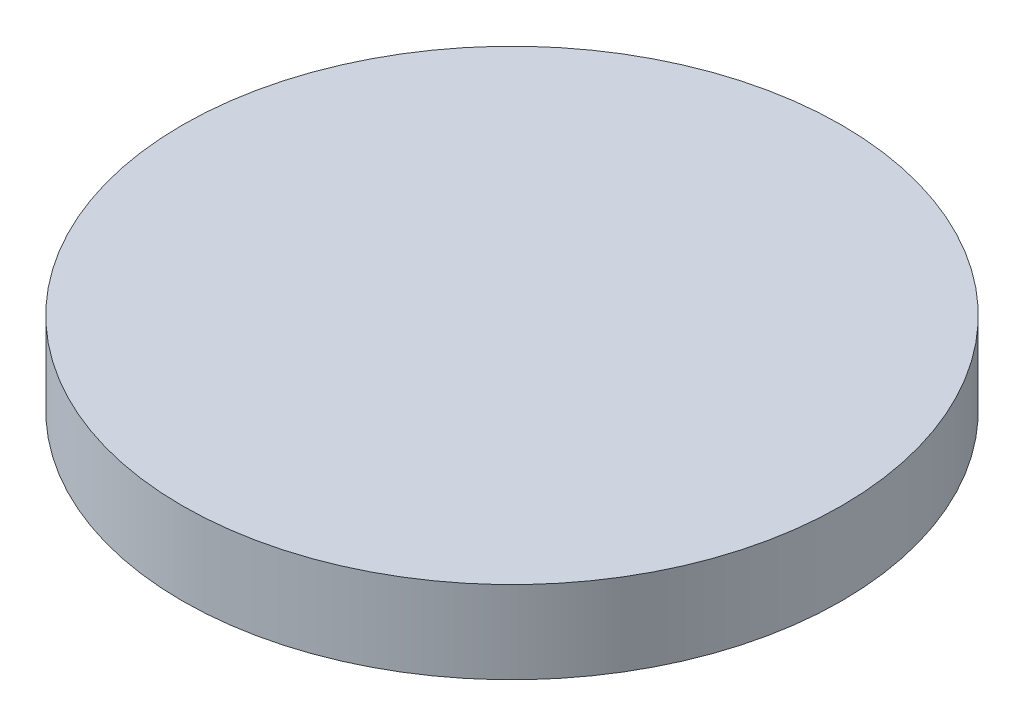
SolidWorks part; units mm, degrees
ref_plane "Front Plane" through (0, 0, 0) normal (0, 0, 1) x (1, 0, 0)
ref_plane "Top Plane" through (0, 0, 0) normal (0, 1, 0) x (1, 0, 0)
ref_plane "Right Plane" through (0, 0, 0) normal (1, 0, 0) x (0, 0, -1)
sketch "Sketch1" plane through (0, 0, 0) normal (0, 1, 0) x (1, 0, 0)
  circle A0 centre (0, 0) radius 101.6
  dimension "D1" = 203.2
extrude "Boss-Extrude1" add sketch "Sketch1" along normal blind 25.4
sketch "Sketch2" plane through (0, 0, 0) normal (0, -1, 0) x (1, 0, 0)
  circle A2 centre (0, 0) radius 19.05
  dimension "D1" = 38.1
extrude "Boss-Extrude2" add sketch "Sketch2" along normal blind 50.8
sketch "Sketch3" plane through (0, -50.8, 0) normal (0, -1, 0) x (1, 0, 0)
  circle A0 centre (0, 0) radius 12.7
  dimension "D1" = 25.4
extrude "Cut-Extrude1" cut sketch "Sketch3" against normal blind 50.8
